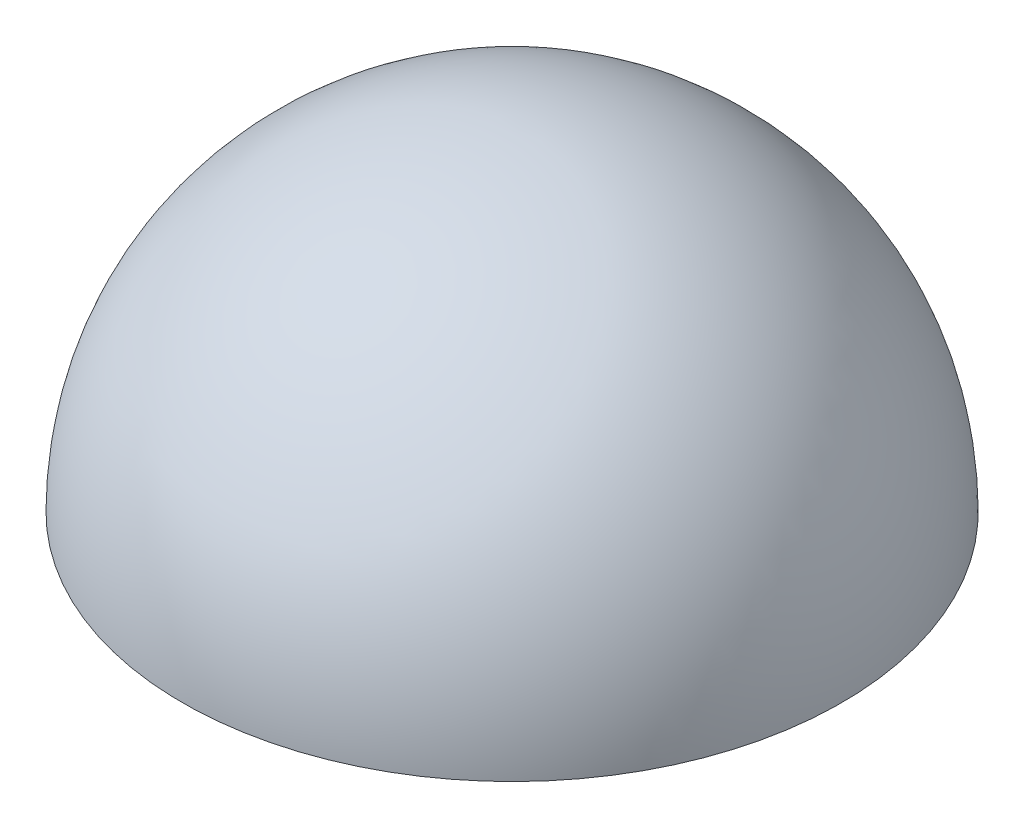
SolidWorks part; units mm, degrees
ref_plane "前视基准面" through (0, 0, 0) normal (0, 0, 1) x (1, 0, 0)
ref_plane "上视基准面" through (0, 0, 0) normal (0, 1, 0) x (1, 0, 0)
ref_plane "右视基准面" through (0, 0, 0) normal (1, 0, 0) x (0, 0, -1)
sketch "草图1" plane through (0, 0, 0) normal (0, 1, 0) x (1, 0, 0)
  line L0 (-10, 0) -> (10, 0)
  arc A0 (10, 0) -> (-10, 0) centre (0, 0) ccw
  dimension "D1" = 20
revolve "旋转1" add sketch "草图1" angle 180 about L0
